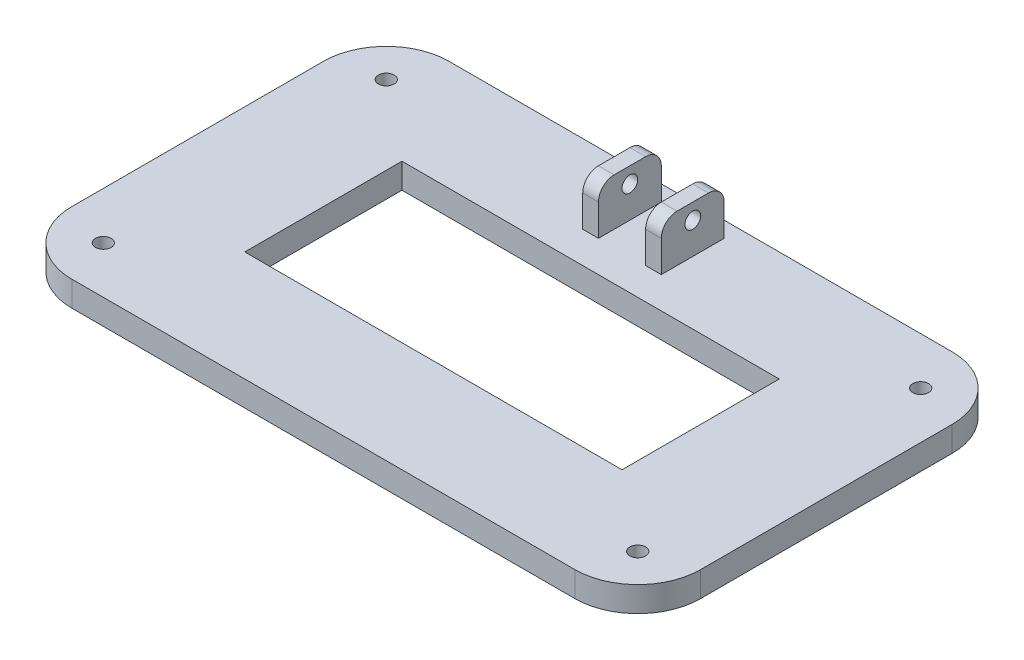
SolidWorks part; units mm, degrees
ref_plane "Front Plane" through (0, 0, 0) normal (0, 0, 1) x (1, 0, 0)
ref_plane "Top Plane" through (0, 0, 0) normal (0, 1, 0) x (1, 0, 0)
ref_plane "Right Plane" through (0, 0, 0) normal (1, 0, 0) x (0, 0, -1)
sketch "Sketch1" plane through (0, 0, 0) normal (0, 1, 0) x (1, 0, 0)
  line L1 (-80, 60) -> (80, 60)
  line L2 (-100, 40) -> (-100, -40)
  line L3 (-80, -60) -> (80, -60)
  line L4 (100, 40) -> (100, -40)
  line L5 (-100, 60) -> (100, -60) construction
  line L6 (-100, -60) -> (100, 60) construction
  line L7 (-60, 25) -> (60, 25)
  line L8 (-60, 25) -> (-60, -25)
  line L9 (-60, -25) -> (60, -25)
  line L10 (60, 25) -> (60, -25)
  line L11 (-60, 25) -> (60, -25) construction
  line L12 (-60, -25) -> (60, 25) construction
  arc A0 (-80, 60) -> (-100, 40) centre (-80, 40) ccw
  arc A1 (-100, -40) -> (-80, -60) centre (-80, -40) ccw
  arc A2 (100, -40) -> (80, -60) centre (80, -40) cw
  arc A3 (100, 40) -> (80, 60) centre (80, 40) ccw
  point P0 (0, 0)
  point P18 (0, 0)
  dimension "D3" = 20
  dimension "D1" = 200
  dimension "D2" = 120
  dimension "D4" = 50
  dimension "D5" = 120
extrude "Boss-Extrude1" add sketch "Sketch1" along normal blind 8
sketch "Sketch2" plane through (0, 8, 0) normal (0, 1, 0) x (1, 0, 0)
  line L0 (0, 0) -> (85, 0)
  line L1 (85, 0) -> (85, -45)
  circle A0 centre (85, -45) radius 2.5
  dimension "D3" = 5
  dimension "D1" = 45
  dimension "D2" = 85
extrude "Cut-Extrude1" cut sketch "Sketch2" against normal blind 10
mirror "Mirror1" about plane through (0, 0, 0) normal (1, 0, 0) of "Cut-Extrude1"
mirror "Mirror2" about plane through (0, 0, 0) normal (0, 0, 1) of "Mirror1", "Cut-Extrude1"
sketch "Sketch4" plane through (0, 8, 0) normal (0, 1, 0) x (1, 0, 0)
  line L0 (0, 0) -> (0, 45)
  line L1 (0, 45) -> (10, 45)
  line L3 (7.5, 55) -> (12.5, 55)
  line L4 (7.5, 55) -> (7.5, 35)
  line L5 (7.5, 35) -> (12.5, 35)
  line L6 (12.5, 55) -> (12.5, 35)
  line L7 (7.5, 55) -> (12.5, 35) construction
  line L8 (7.5, 35) -> (12.5, 55) construction
  dimension "D1" = 45
  dimension "D2" = 20
  dimension "D3" = 5
  dimension "D4" = 10
extrude "Boss-Extrude2" add sketch "Sketch4" along normal blind 15
fillet "Fillet1" radius 5 2 edges at (10, 23, -55) (10, 23, -35)
mirror "Mirror4" about plane through (0, 0, 0) normal (1, 0, 0) of "Fillet1", "Boss-Extrude2"
sketch "Sketch5" plane through (12.5, 0, 0) normal (1, 0, 0) x (0, 0, -1)
  line L0 (45, 23) -> (45, 18) construction
  line L1 (50, 23) -> (40, 23) construction
  circle A0 centre (45, 18) radius 2.5
  dimension "D1" = 5
  dimension "D2" = 5
extrude "Cut-Extrude2" cut sketch "Sketch5" against normal blind 54
